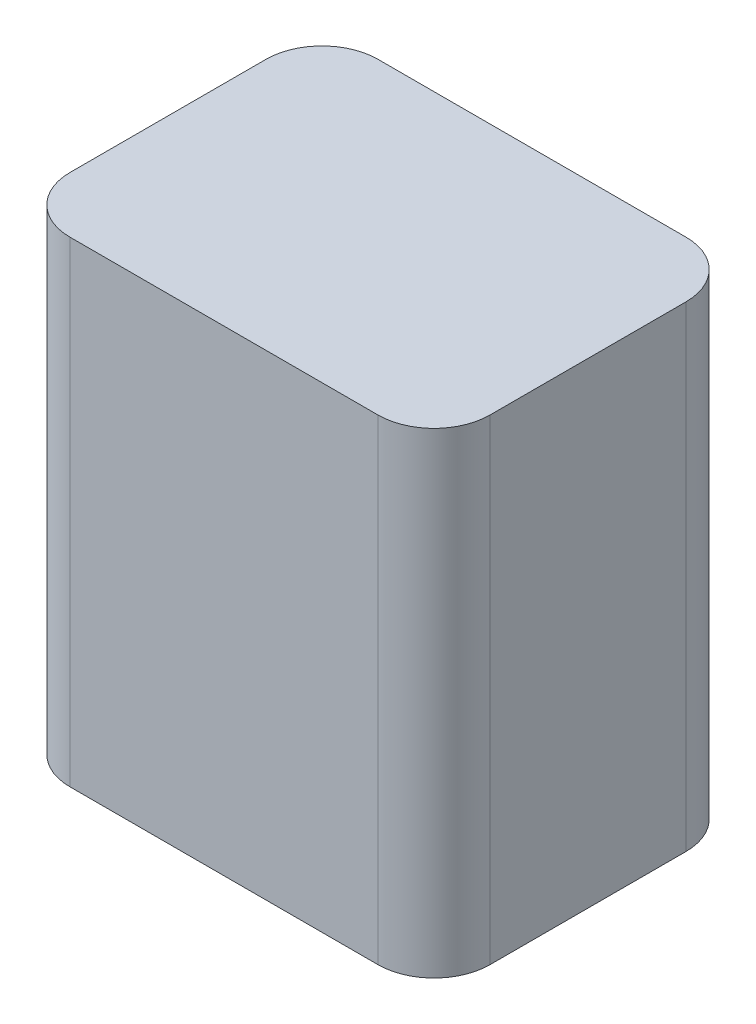
SolidWorks part; units mm, degrees
ref_plane "Alzado" through (0, 0, 0) normal (0, 0, 1) x (1, 0, 0)
ref_plane "Planta" through (0, 0, 0) normal (0, 1, 0) x (1, 0, 0)
ref_plane "Vista lateral" through (0, 0, 0) normal (1, 0, 0) x (0, 0, -1)
sketch "Croquis1" plane through (0, 0, 0) normal (0, 0, 1) x (1, 0, 0)
  line L1 (-20.52, 8.5316) -> (-5.52, 8.5316)
  line L2 (-20.52, 8.5316) -> (-20.52, -8.4684)
  line L3 (-20.52, -8.4684) -> (-5.52, -8.4684)
  line L4 (-5.52, 8.5316) -> (-5.52, -8.4684)
  dimension "D1" = 17
  dimension "D2" = 15
extrude "Saliente-Extruir1" add sketch "Croquis1" along normal blind 11
fillet "Redondeo1" radius 2 4 edges at (-5.52, 0.0316, 0) (-5.52, 0.0316, 11) (-20.52, 0.0316, 0) (-20.52, 0.0316, 11)
